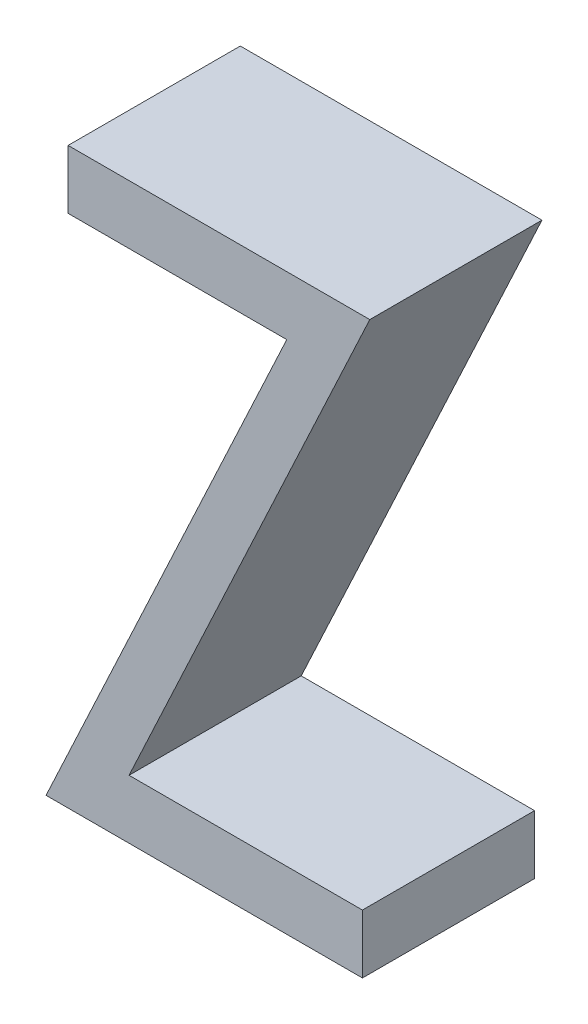
SolidWorks part; units mm, degrees
ref_plane "Plan de face" through (0, 0, 0) normal (0, 0, 1) x (1, 0, 0)
ref_plane "Plan de dessus" through (0, 0, 0) normal (0, 1, 0) x (1, 0, 0)
ref_plane "Plan de droite" through (0, 0, 0) normal (1, 0, 0) x (0, 0, -1)
sketch "Esquisse1" plane through (0, 0, 0) normal (0, 0, 1) x (1, 0, 0)
  text T0 "Z" font "Century Gothic" height 5
extrude "Boss.-Extru.1" add sketch "Esquisse1" along normal blind 1.5
